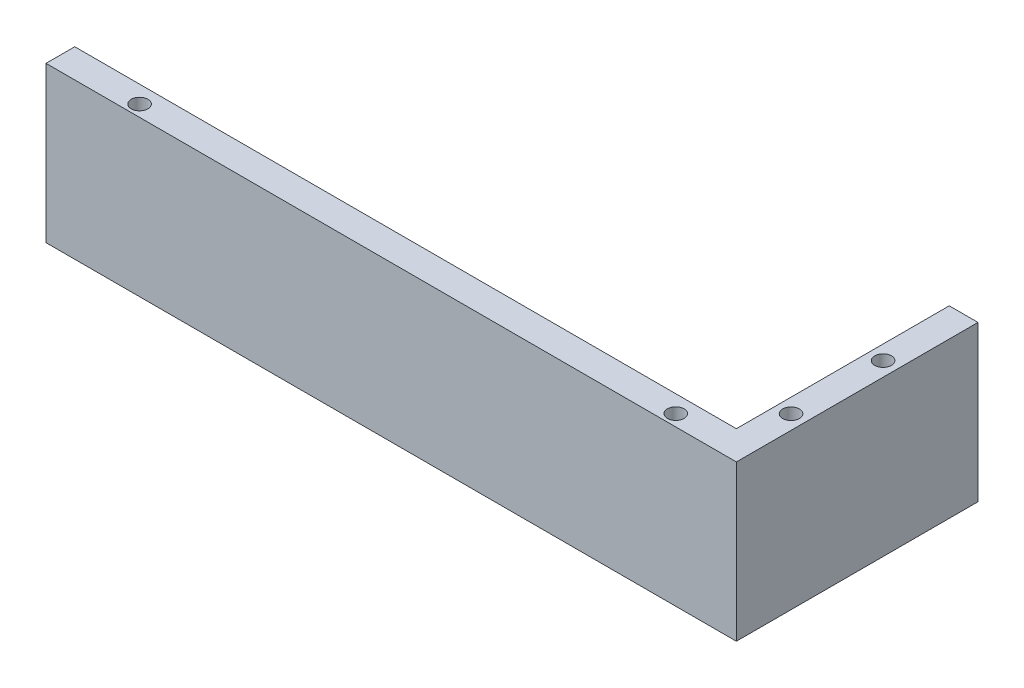
SolidWorks part; units mm, degrees
ref_plane "前视基准面" through (0, 0, 0) normal (0, 0, 1) x (1, 0, 0)
ref_plane "上视基准面" through (0, 0, 0) normal (0, 1, 0) x (1, 0, 0)
ref_plane "右视基准面" through (0, 0, 0) normal (1, 0, 0) x (0, 0, -1)
sketch "草图1" plane through (0, 0, 0) normal (0, 1, 0) x (1, 0, 0)
  line L1 (2.5, -20) -> (-2.5, -20)
  line L2 (2.5, -20) -> (2.5, 20)
  line L3 (2.5, 20) -> (-2.5, 20)
  line L4 (-2.5, -20) -> (-2.5, 20)
  line L5 (2.5, -20) -> (-2.5, 20) construction
  line L6 (2.5, 20) -> (-2.5, -20) construction
  circle A0 centre (0, -10) radius 1.45
  circle A1 centre (0, 6) radius 1.45
  point P0 (0, 0)
  dimension "D3" = 10
  dimension "D4" = 2.9
  dimension "D5" = 16
  dimension "D1" = 40
  dimension "D2" = 5
extrude "凸台-拉伸1" add sketch "草图1" along normal blind 27 contours L4 L1 L2 L3 A1 A0
sketch "草图2" plane through (0, 0, 0) normal (0, 1, 0) x (1, 0, 0)
  line L1 (2.5, -22) -> (-117.5, -22)
  line L2 (2.5, -22) -> (2.5, -17)
  line L3 (2.5, -17) -> (-117.5, -17)
  line L4 (-117.5, -22) -> (-117.5, -17)
  circle A2 centre (-10.04, -20) radius 1.45
  circle A3 centre (-103.24, -20) radius 1.45
  dimension "D3" = 2.9
  dimension "D1" = 5
  dimension "D2" = 120
  dimension "D6" = 93.2
extrude "凸台-拉伸2" add sketch "草图2" along normal blind 27
